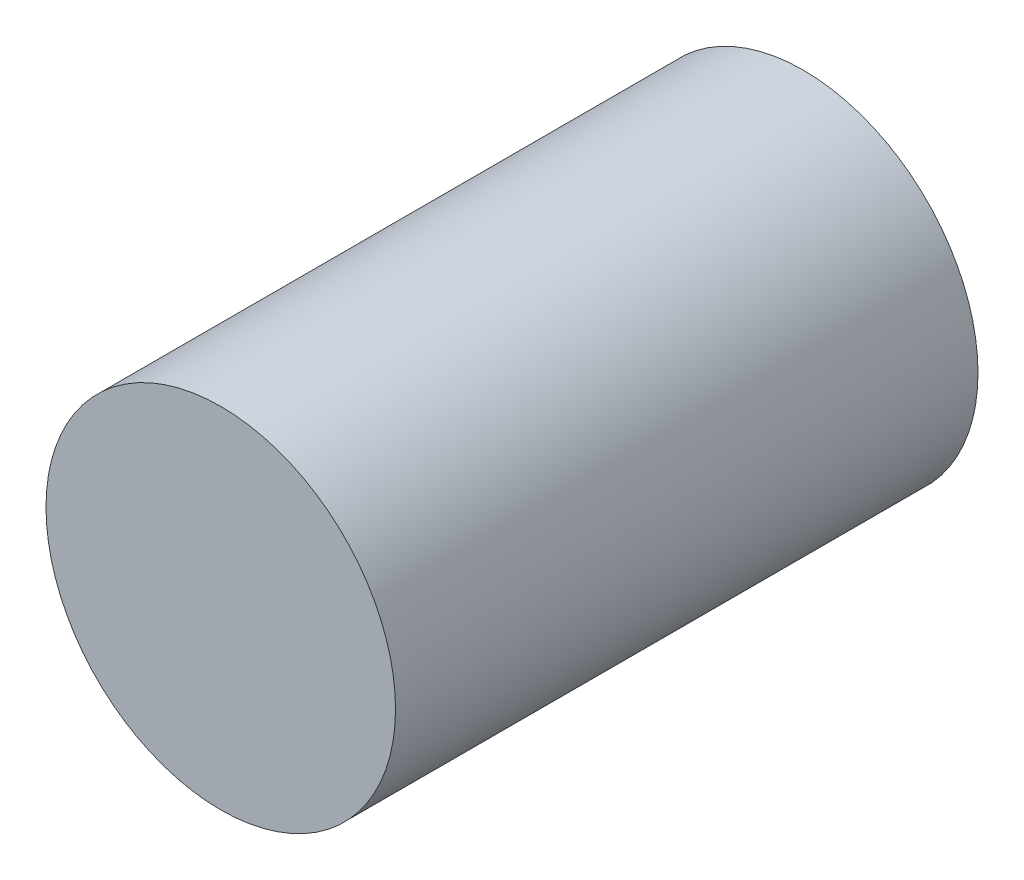
SolidWorks part; units mm, degrees
ref_plane "Front" through (0, 0, 0) normal (0, 0, 1) x (1, 0, 0)
ref_plane "Top" through (0, 0, 0) normal (0, 1, 0) x (1, 0, 0)
ref_plane "Right" through (0, 0, 0) normal (1, 0, 0) x (0, 0, -1)
sketch "草图3" plane through (0, 0, 0) normal (0, 0, 1) x (1, 0, 0)
  circle A0 centre (0, 0) radius 0.03
  dimension "D1" = 0.06
extrude "凸台-拉伸2" add sketch "草图3" along normal blind 0.1 contours A0
